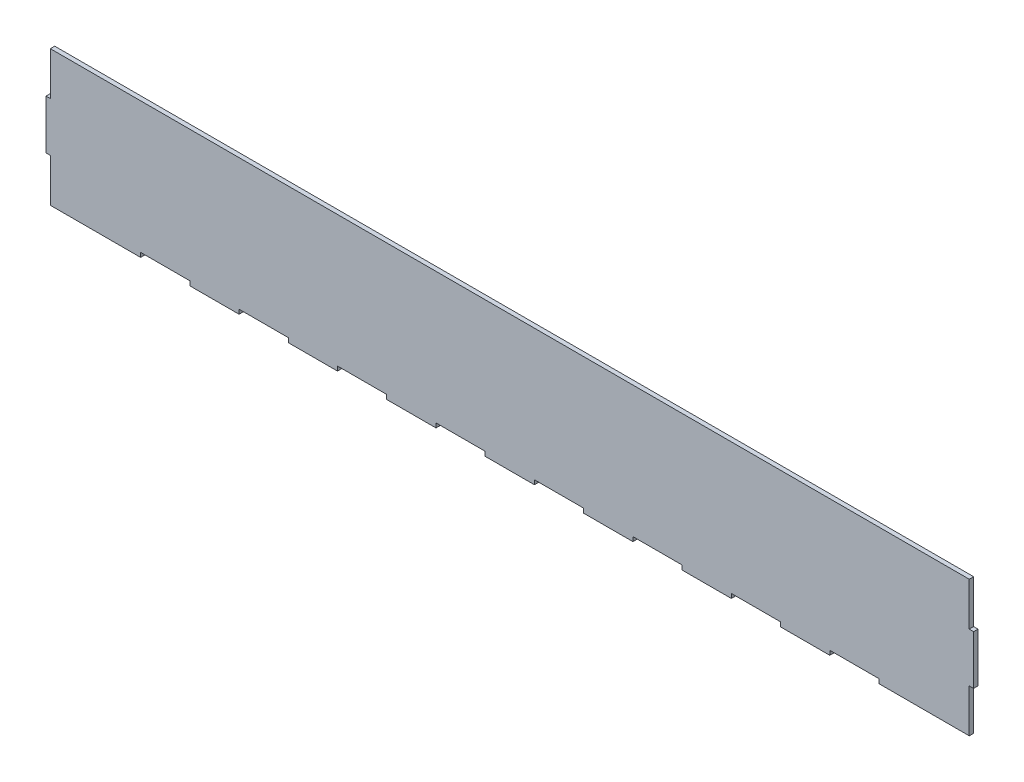
SolidWorks part; units mm, degrees
ref_plane "Front Plane" through (0, 0, 0) normal (0, 0, 1) x (1, 0, 0)
ref_plane "Top Plane" through (0, 0, 0) normal (0, 1, 0) x (1, 0, 0)
ref_plane "Right Plane" through (0, 0, 0) normal (1, 0, 0) x (0, 0, -1)
sketch "Model" plane through (0, 0, 0) normal (0, 0, 1) x (1, 0, 0)
  line L0 (642, 192) -> (642, 162.375)
  line L1 (642, 162.375) -> (639, 162.375)
  line L2 (639, 162.375) -> (639, 128.625)
  line L3 (639, 128.625) -> (642, 128.625)
  line L4 (642, 128.625) -> (642, 99)
  line L5 (642, 99) -> (703.875, 99)
  line L6 (703.875, 99) -> (703.875, 102)
  line L7 (703.875, 102) -> (737.625, 102)
  line L8 (737.625, 102) -> (737.625, 99)
  line L9 (737.625, 99) -> (771.375, 99)
  line L10 (771.375, 99) -> (771.375, 102)
  line L11 (771.375, 102) -> (805.125, 102)
  line L12 (805.125, 102) -> (805.125, 99)
  line L13 (805.125, 99) -> (838.875, 99)
  line L14 (838.875, 99) -> (838.875, 102)
  line L15 (838.875, 102) -> (872.625, 102)
  line L16 (872.625, 102) -> (872.625, 99)
  line L17 (872.625, 99) -> (906.375, 99)
  line L18 (906.375, 99) -> (906.375, 102)
  line L19 (906.375, 102) -> (940.125, 102)
  line L20 (940.125, 102) -> (940.125, 99)
  line L21 (940.125, 99) -> (973.875, 99)
  line L22 (973.875, 99) -> (973.875, 102)
  line L23 (973.875, 102) -> (1007.625, 102)
  line L24 (1007.625, 102) -> (1007.625, 99)
  line L25 (1007.625, 99) -> (1041.375, 99)
  line L26 (1041.375, 99) -> (1041.375, 102)
  line L27 (1041.375, 102) -> (1075.125, 102)
  line L28 (1075.125, 102) -> (1075.125, 99)
  line L29 (1075.125, 99) -> (1108.875, 99)
  line L30 (1108.875, 99) -> (1108.875, 102)
  line L31 (1108.875, 102) -> (1142.625, 102)
  line L32 (1142.625, 102) -> (1142.625, 99)
  line L33 (1142.625, 99) -> (1176.375, 99)
  line L34 (1176.375, 99) -> (1176.375, 102)
  line L35 (1176.375, 102) -> (1210.125, 102)
  line L36 (1210.125, 102) -> (1210.125, 99)
  line L37 (1210.125, 99) -> (1243.875, 99)
  line L38 (1243.875, 99) -> (1272, 99)
  line L39 (1272, 99) -> (1272, 128.625)
  line L40 (1272, 128.625) -> (1275, 128.625)
  line L41 (1275, 128.625) -> (1275, 162.375)
  line L42 (1275, 162.375) -> (1272, 162.375)
  line L43 (1272, 162.375) -> (1272, 192)
  line L44 (1272, 192) -> (642, 192)
extrude "Boss-Extrude1" add sketch "Model" along normal blind 3
